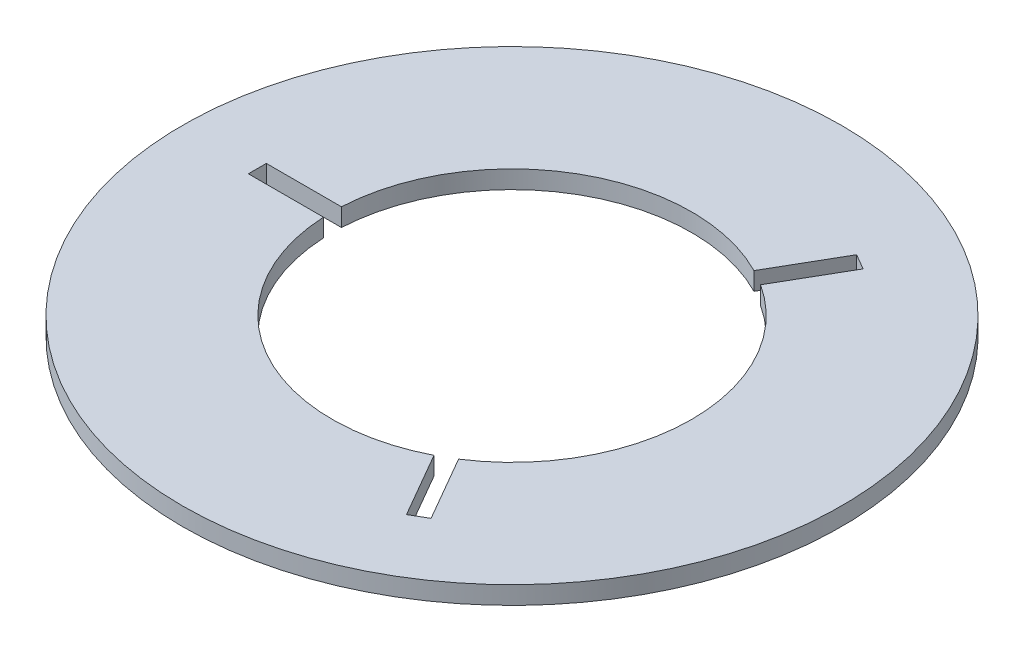
SolidWorks part; units mm, degrees
ref_plane "Front Plane" through (0, 0, 0) normal (0, 0, 1) x (1, 0, 0)
ref_plane "Top Plane" through (0, 0, 0) normal (0, 1, 0) x (1, 0, 0)
ref_plane "Right Plane" through (0, 0, 0) normal (1, 0, 0) x (0, 0, -1)
sketch "Sketch1" plane through (0, 0, 0) normal (0, 1, 0) x (1, 0, 0)
  circle A0 centre (0, 0) radius 55
  dimension "D1" = 110
extrude "Boss-Extrude1" add sketch "Sketch1" along normal blind 3
sketch "Sketch2" plane through (0, 3, 0) normal (0, 1, 0) x (1, 0, 0)
  circle A0 centre (0, 0) radius 30
  dimension "D1" = 60
extrude "Cut-Extrude1" cut sketch "Sketch2" against normal blind 3
sketch "Sketch3" plane through (0, 3, 0) normal (0, 1, 0) x (1, 0, 0)
  line L0 (73.8169, 0) -> (-73.8169, 0) construction
  line L1 (0, -87.0918) -> (0, 87.0918) construction
  line L3 (-42.5, 1.5) -> (-17.5, 1.5)
  line L4 (-42.5, 1.5) -> (-42.5, -1.5)
  line L5 (-42.5, -1.5) -> (-17.5, -1.5)
  line L6 (-17.5, 1.5) -> (-17.5, -1.5)
  line L7 (-42.5, 1.5) -> (-17.5, -1.5) construction
  line L8 (-42.5, -1.5) -> (-17.5, 1.5) construction
  circle A0 centre (0, 0) radius 30 construction
  point P0 (-30, 0)
  point P6 (0, 0)
  point P10 (0, 0)
  dimension "D1" = 3
  dimension "D2" = 25
extrude "Cut-Extrude2" cut sketch "Sketch3" against normal blind 3
pattern_circular "CirPattern1" count 3 over 360 about axis through (0, 0, 0) along (0, 1, 0) of "Cut-Extrude2"
